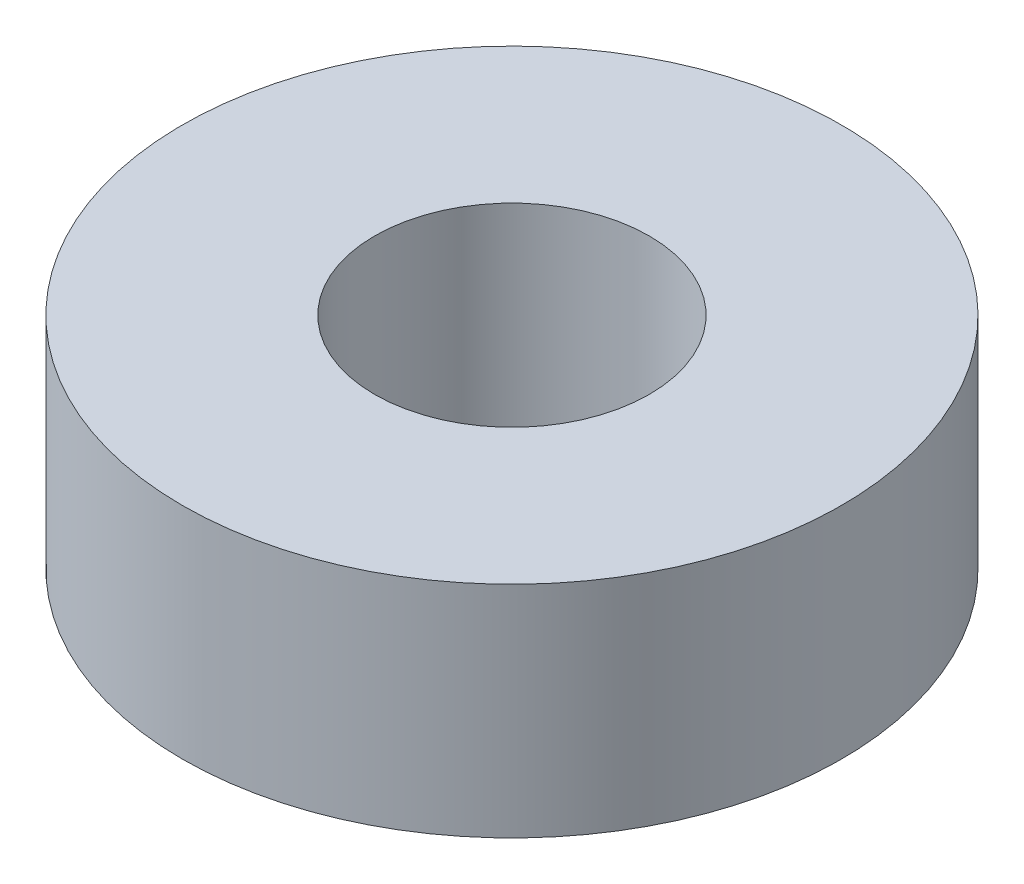
SolidWorks part; units mm, degrees
ref_plane "Спереди" through (0, 0, 0) normal (0, 0, 1) x (1, 0, 0)
ref_plane "Сверху" through (0, 0, 0) normal (0, 1, 0) x (1, 0, 0)
ref_plane "Справа" through (0, 0, 0) normal (1, 0, 0) x (0, 0, -1)
sketch "Эскиз1" plane through (0, 0, 0) normal (0, 1, 0) x (1, 0, 0)
  circle A0 centre (0, 0) radius 1.25
  circle A1 centre (0, 0) radius 3
  dimension "D1" = 6
  dimension "D2" = 2.5
extrude "Бобышка-Вытянуть1" add sketch "Эскиз1" along normal blind 2
